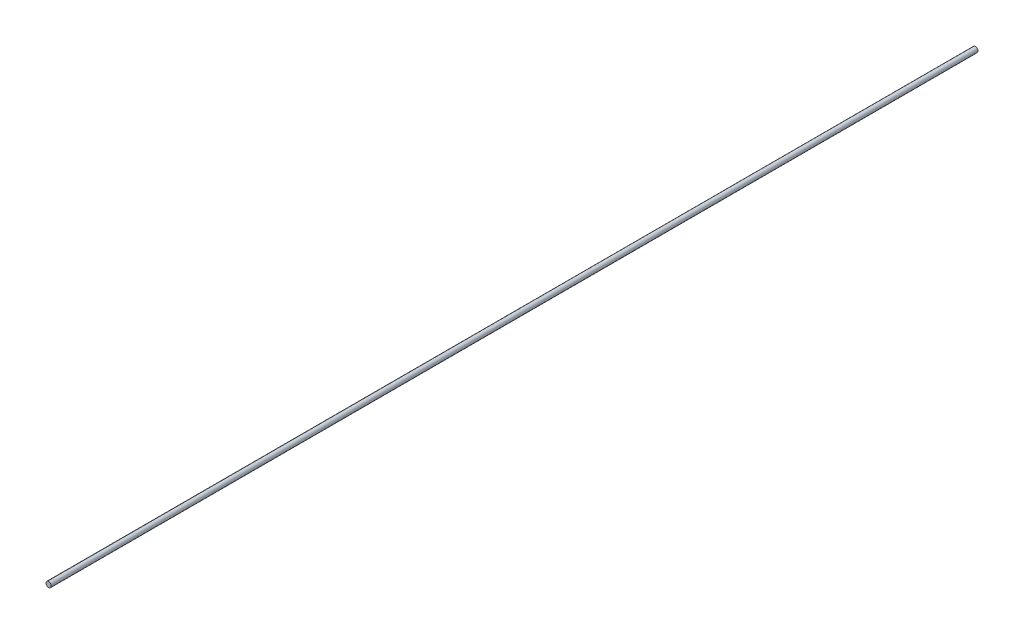
SolidWorks part; units mm, degrees
ref_plane "Front Plane" through (0, 0, 0) normal (0, 0, 1) x (1, 0, 0)
ref_plane "Top Plane" through (0, 0, 0) normal (0, 1, 0) x (1, 0, 0)
ref_plane "Right Plane" through (0, 0, 0) normal (1, 0, 0) x (0, 0, -1)
sketch "Sketch1" plane through (0, 0, 0) normal (0, 0, 1) x (1, 0, 0)
  circle A0 centre (0, 0) radius 12.7
  dimension "D1" = 25.4
extrude "Boss-Extrude1" add sketch "Sketch1" along normal blind 4488.434 contours A0
equation "\"d\" = 1in"
equation "\"A\"= ( 0.25 ) * ( 3.14 ) * ( \"d\" ^ 2 )"
equation "\"Def\"= 0.009in"
equation "\"P\"= 400"
equation "\"E\"= 10 * 10 ^ 6"
equation "\"L\"= ( ( \"Def\" ) * ( \"E\" ) * ( \"A\" ) ) / ( \"P\" )"
